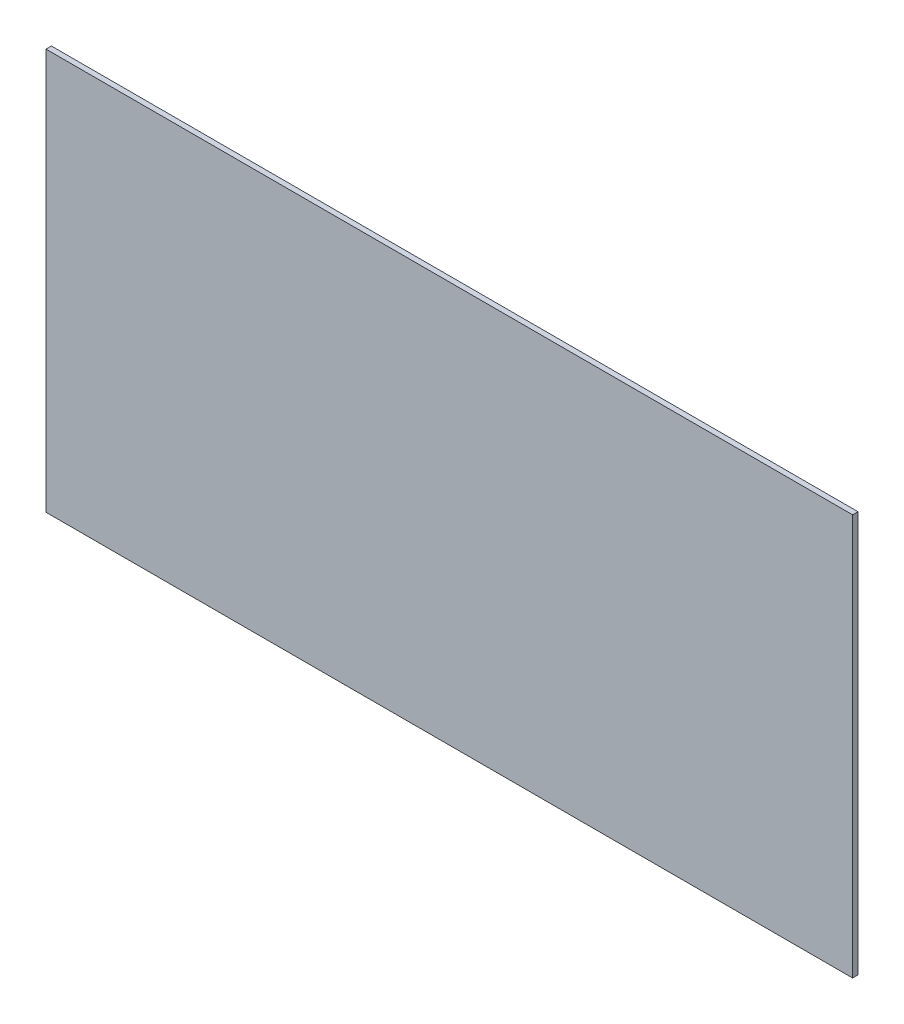
SolidWorks part; units mm, degrees
ref_plane "Спереди" through (0, 0, 0) normal (0, 0, 1) x (1, 0, 0)
ref_plane "Сверху" through (0, 0, 0) normal (0, 1, 0) x (1, 0, 0)
ref_plane "Справа" through (0, 0, 0) normal (1, 0, 0) x (0, 0, -1)
sketch "Эскиз1" plane through (0, 0, 0) normal (0, 0, 1) x (1, 0, 0)
  line L1 (0, 0) -> (1498, 0)
  line L2 (0, 0) -> (0, 745)
  line L3 (0, 745) -> (1498, 745)
  line L4 (1498, 0) -> (1498, 745)
  dimension "D1" = 1498
  dimension "D2" = 745
extrude "Бобышка-Вытянуть1" add sketch "Эскиз1" along normal blind 10
